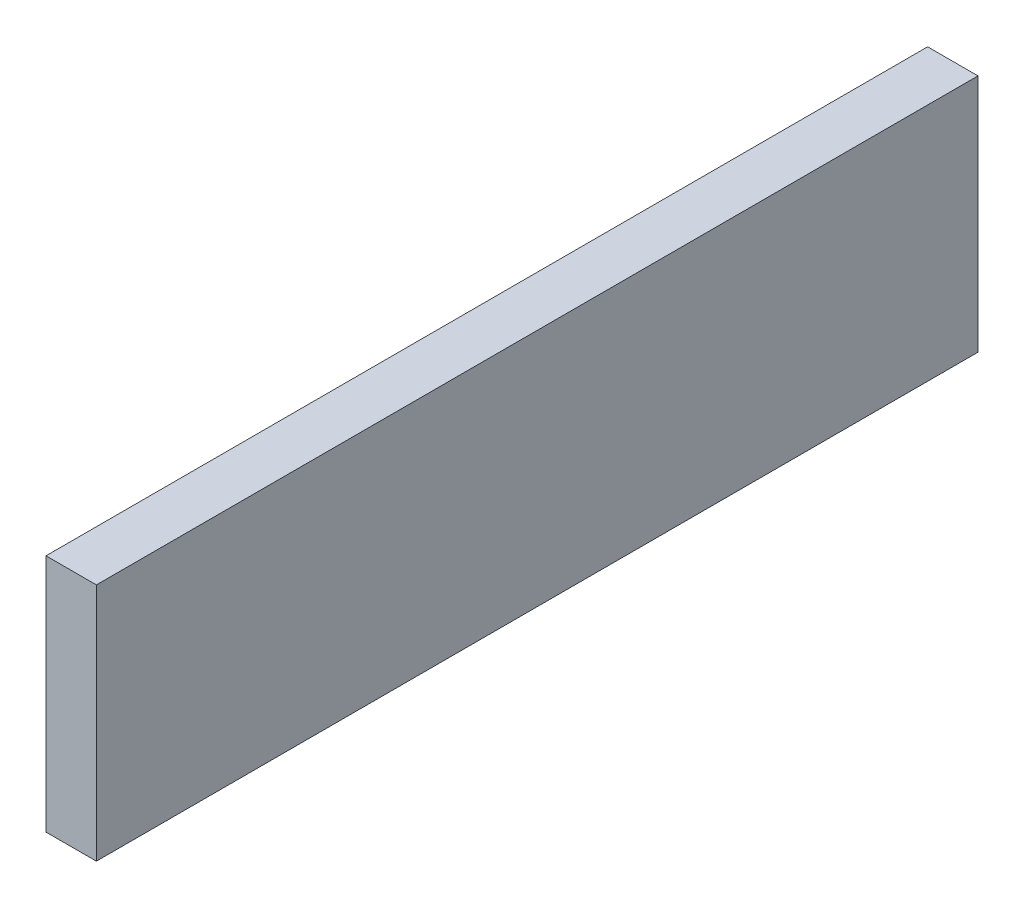
SolidWorks part; units mm, degrees
ref_plane "front" through (0, 0, 0) normal (0, 0, 1) x (1, 0, 0)
ref_plane "top" through (0, 0, 0) normal (0, 1, 0) x (1, 0, 0)
ref_plane "right" through (0, 0, 0) normal (1, 0, 0) x (0, 0, -1)
sketch "Sketch1" plane through (0, 0, 0) normal (0, 0, 1) x (1, 0, 0)
  line L1 (-12.7, 120.65) -> (12.7, 120.65)
  line L2 (-12.7, 120.65) -> (-12.7, 0)
  line L3 (-12.7, 0) -> (12.7, 0)
  line L4 (12.7, 120.65) -> (12.7, 0)
  dimension "D1" = 25.4
  dimension "D2" = 120.65
extrude "Extrude1" add sketch "Sketch1" against normal blind 444.5
